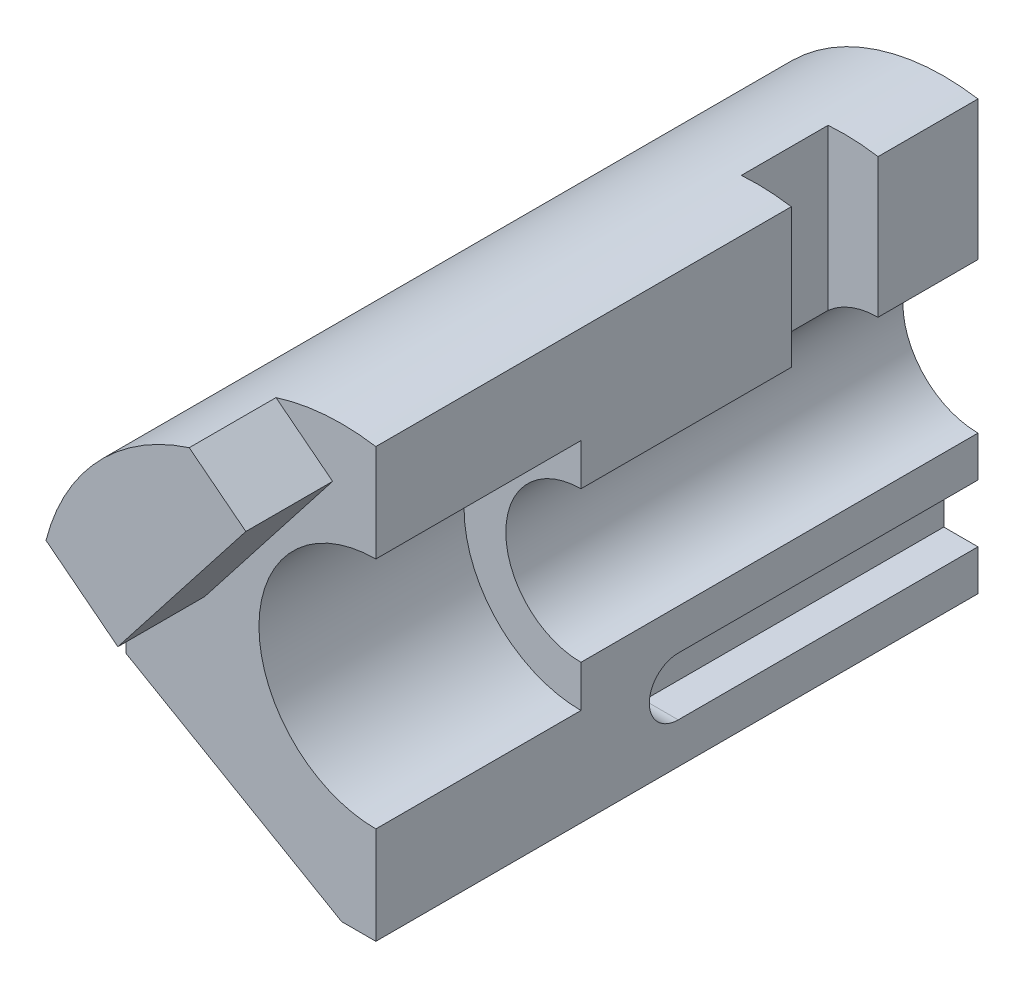
SolidWorks part; units mm, degrees
material "1060 Alloy"
ref_plane "Front Plane" through (0, 0, 0) normal (0, 0, 1) x (1, 0, 0)
ref_plane "Top Plane" through (0, 0, 0) normal (0, 1, 0) x (1, 0, 0)
ref_plane "Right Plane" through (0, 0, 0) normal (1, 0, 0) x (0, 0, -1)
sketch "Sketch1" plane through (0, 0, 0) normal (0, 0, 1) x (1, 0, 0)
  line L0 (0, 0) -> (-13, 0)
  line L1 (-13, 0) -> (-95, 47.3427)
  line L2 (0, 162.963) -> (0, 0)
  line L3 (-95, 47.3427) -> (-95, 82)
  arc A2 (-95, 82) -> (0, 162.963) centre (-13, 82) cw
  dimension "D1" = 82
  dimension "D2" = 13
  dimension "D3" = 82
  dimension "D4" = 30
  dimension "D5" = 82
extrude "Boss-Extrude1" add sketch "Sketch1" along normal blind 229
sketch "Sketch2" plane through (0, 0, 229) normal (0, 0, 1) x (1, 0, 0)
  line L0 (0, 0) -> (0, 162.963) construction
  circle A0 centre (0, 81.4815) radius 44.45
  dimension "D1" = 88.9
extrude "Cut-Extrude1" cut sketch "Sketch2" against normal blind 78
sketch "Sketch3" plane through (0, 0, 151) normal (0, 0, 1) x (1, 0, 0)
  line L0 (0, 37.0315) -> (0, 125.9315) construction
  circle A0 centre (0, 81.4815) radius 28.575
  dimension "D1" = 57.15
extrude "Cut-Extrude2" cut sketch "Sketch3" against normal through all
sketch "Sketch4" plane through (0, 0, 0) normal (1, 0, 0) x (0, 0, -1)
  line L0 (0, 26.4532) -> (-114, 26.4532) construction
  line L1 (0, 0) -> (0, 52.9065) construction
  line L2 (0, 15.4532) -> (-114, 15.4532)
  line L3 (0, 37.4532) -> (-114, 37.4532)
  arc A0 (0, 15.4532) -> (0, 37.4532) centre (0, 26.4532) ccw
  arc A1 (-114, 37.4532) -> (-114, 15.4532) centre (-114, 26.4532) ccw
  point P4 (-57, 26.4532)
  dimension "D1" = 11
  dimension "D2" = 114
extrude "Cut-Extrude3" cut sketch "Sketch4" against normal blind 13
sketch "Sketch5" plane through (0, 0, 229) normal (0, 0, 1) x (1, 0, 0)
  line L0 (0, 81.4815) -> (-72.6632, 138.2522) construction
  line L1 (-37.9723, 160.105) -> (-16.4375, 143.2801)
  line L2 (-16.4375, 143.2801) -> (-65.1086, 80.9841)
  line L3 (-65.1086, 80.9841) -> (-92.4382, 102.3363)
  line L4 (-13, 0) -> (0, 0) construction
  line L10 (0, 0) -> (0, 37.0315)
  line L11 (0, 125.9315) -> (0, 162.963)
  line L12 (-95, 82) -> (-95, 47.3427)
  line L13 (-95, 47.3427) -> (-13, 0)
  line L14 (-13, 0) -> (0, 0)
  arc A0 (0, 162.963) -> (-95, 82) centre (-13, 82) ccw construction
  arc A3 (0, 125.9315) -> (0, 37.0315) centre (0, 81.4815) ccw
  arc A4 (0, 162.963) -> (-95, 82) centre (-13, 82) ccw
  arc A6 (-37.9723, 160.105) -> (-92.4382, 102.3363) centre (-13, 82) ccw
  dimension "D1" = 41
  dimension "D2" = 41
  dimension "D3" = 38
  dimension "D4" = 51
  dimension "D5" = 38
  dimension "D6" = 38
  dimension "D7" = 0
extrude "Boss-Extrude2" add sketch "Sketch5" along normal blind 33
ref_plane "Plane1" through (0, 164, 0) normal (0, 1, 0) x (1, 0, 0)
sketch "Sketch7" plane through (0, 164, 0) normal (0, 1, 0) x (1, 0, 0)
  line L0 (0, -229) -> (0, 0) construction
  line L1 (0, -71) -> (-19, -71)
  line L2 (0, -71) -> (0, -38)
  line L3 (0, -38) -> (-19, -38)
  line L4 (-19, -71) -> (-19, -38)
  line L5 (0, 0) -> (-95, 0) construction
  dimension "D1" = 19
  dimension "D2" = 38
  dimension "D3" = 33
extrude "Cut-Extrude4" cut sketch "Sketch7" against normal up to surface (61.1754 mm away)
equation "\"a\"= 229mm"
equation "\"b\"= 114mm"
equation "\"c\"= 82mm"
equation "\"D3@Sketch1\"=\"c\""
equation "\"D1@Sketch1\"=\"c\""
equation "\"D5@Sketch1\"=\"c\""
equation "\"D1@Boss-Extrude1\"=\"a\""
equation "\"D2@Sketch4\"=\"b\""
